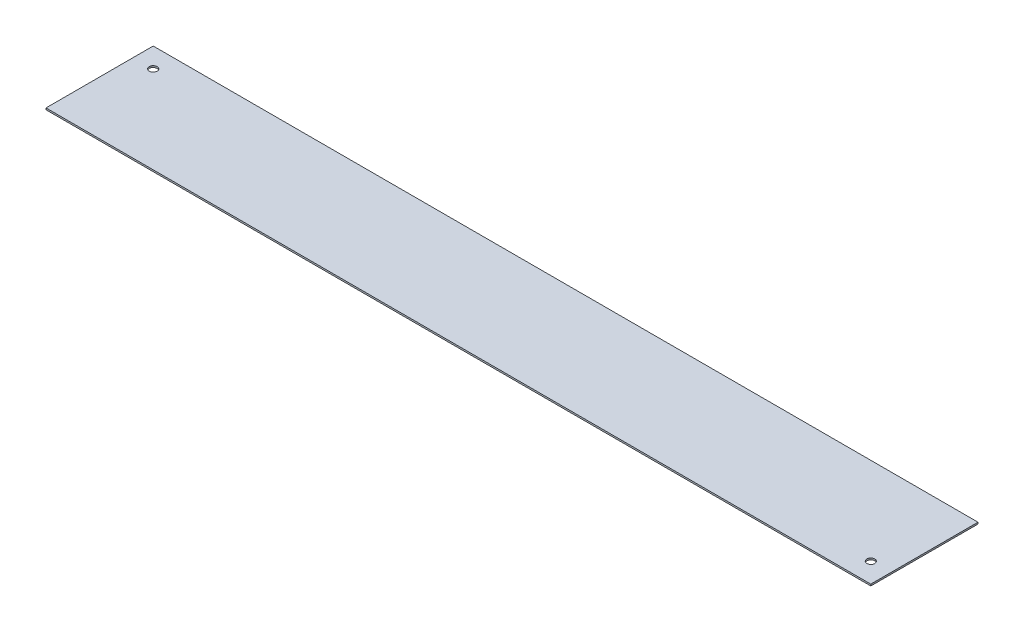
SolidWorks part; units mm, degrees
ref_plane "Front Plane" through (0, 0, 0) normal (0, 0, 1) x (1, 0, 0)
ref_plane "Top Plane" through (0, 0, 0) normal (0, 1, 0) x (1, 0, 0)
ref_plane "Right Plane" through (0, 0, 0) normal (1, 0, 0) x (0, 0, -1)
sketch "Sketch1" plane through (0, 0, 0) normal (0, 1, 0) x (1, 0, 0)
  line L1 (-427.5551, 35.3634) -> (72.4449, 35.3634)
  line L2 (-427.5551, 35.3634) -> (-427.5551, -29.6366)
  line L3 (-427.5551, -29.6366) -> (72.4449, -29.6366)
  line L4 (72.4449, 35.3634) -> (72.4449, -29.6366)
  dimension "D1" = 65
  dimension "D2" = 500
extrude "Boss-Extrude1" add sketch "Sketch1" along normal blind 1
hole_wizard "M4 Clearance Slot1" positions "Sketch2" profile "Sketch3" size "M4" standard "ANSI Metric" slot yes end condition through all
sketch "Sketch2" plane through (0, 1, 0) normal (0, 1, 0) x (1, 0, 0)
  line L0 (72.4449, 35.3634) -> (-427.5551, 35.3634) construction
  line L1 (-427.5551, 35.3634) -> (-427.5551, -29.6366) construction
  line L2 (72.4449, -29.6366) -> (72.4449, 35.3634) construction
  line L3 (-427.5551, -29.6366) -> (72.4449, -29.6366) construction
  point P0 (-415.5551, 23.3634)
  point P2 (60.4449, -17.6366)
  dimension "D1" = 12
  dimension "D2" = 12
  dimension "D3" = 12
  dimension "D4" = 12
sketch "Sketch3" plane through (-415.5551, 1, -23.3634) normal (1, 0, 0) x (0, 0, 1)
  line L0 (0, 0) -> (0, 1)
  line L1 (0, 1) -> (2.4, 1)
  line L2 (2.4, 1) -> (2.4, 0)
  line L5 (2.4, 0) -> (0, 0)
  line L11 (0, -6.35) -> (0, 107.95) construction
  dimension "Thru Hole Dia." = 4.8
  dimension "Thru Hole Depth" = 1
